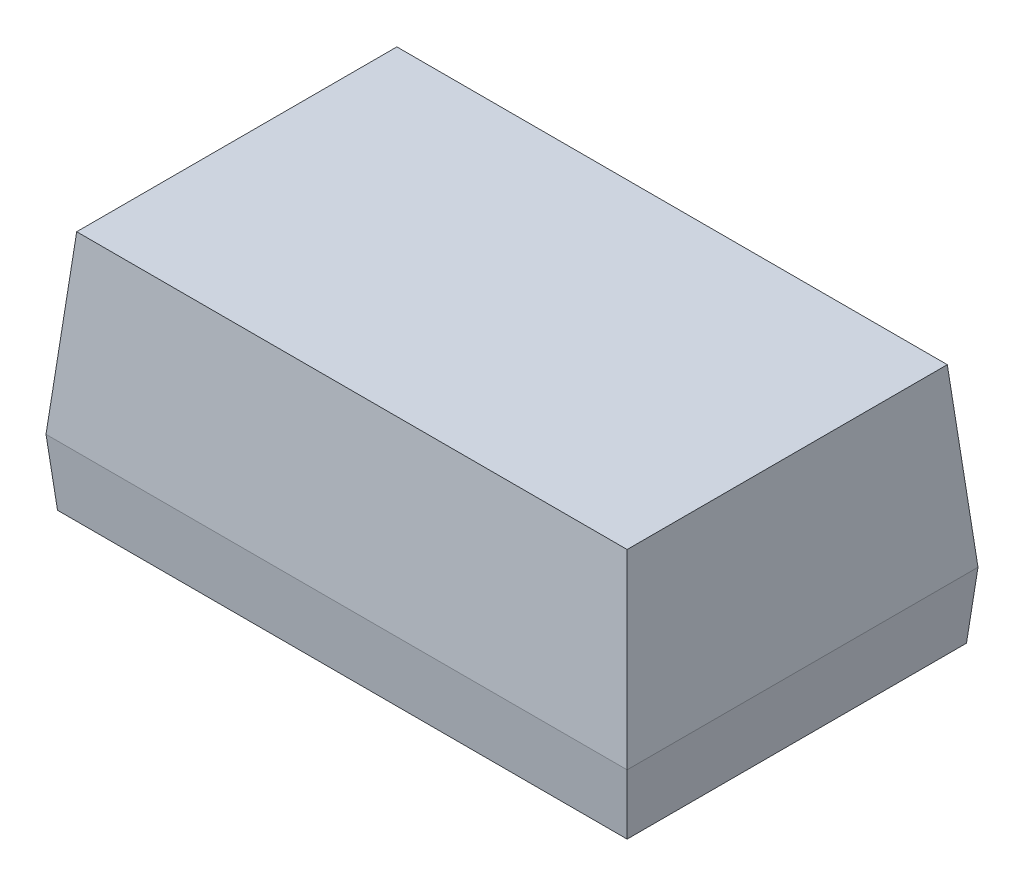
SolidWorks part; units mm, degrees
ref_plane "Front Plane" through (0, 0, 0) normal (0, 0, 1) x (1, 0, 0)
ref_plane "Top Plane" through (0, 0, 0) normal (0, 1, 0) x (1, 0, 0)
ref_plane "Right Plane" through (0, 0, 0) normal (1, 0, 0) x (0, 0, -1)
sketch "Sketch1" plane through (0, 0, 0) normal (0, 1, 0) x (1, 0, 0)
  line L1 (-1.325, 0.8) -> (1.325, 0.8)
  line L2 (-1.325, 0.8) -> (-1.325, -0.8)
  line L3 (-1.325, -0.8) -> (1.325, -0.8)
  line L4 (1.325, 0.8) -> (1.325, -0.8)
  line L5 (-1.325, 0.8) -> (1.325, -0.8) construction
  line L6 (-1.325, -0.8) -> (1.325, 0.8) construction
  point P0 (0, 0)
  dimension "D1" = 1.6
  dimension "D2" = 2.65
extrude "Boss-Extrude1" add sketch "Sketch1" along normal blind 0.8 draft 5 and the other way blind 0.3 draft 5
